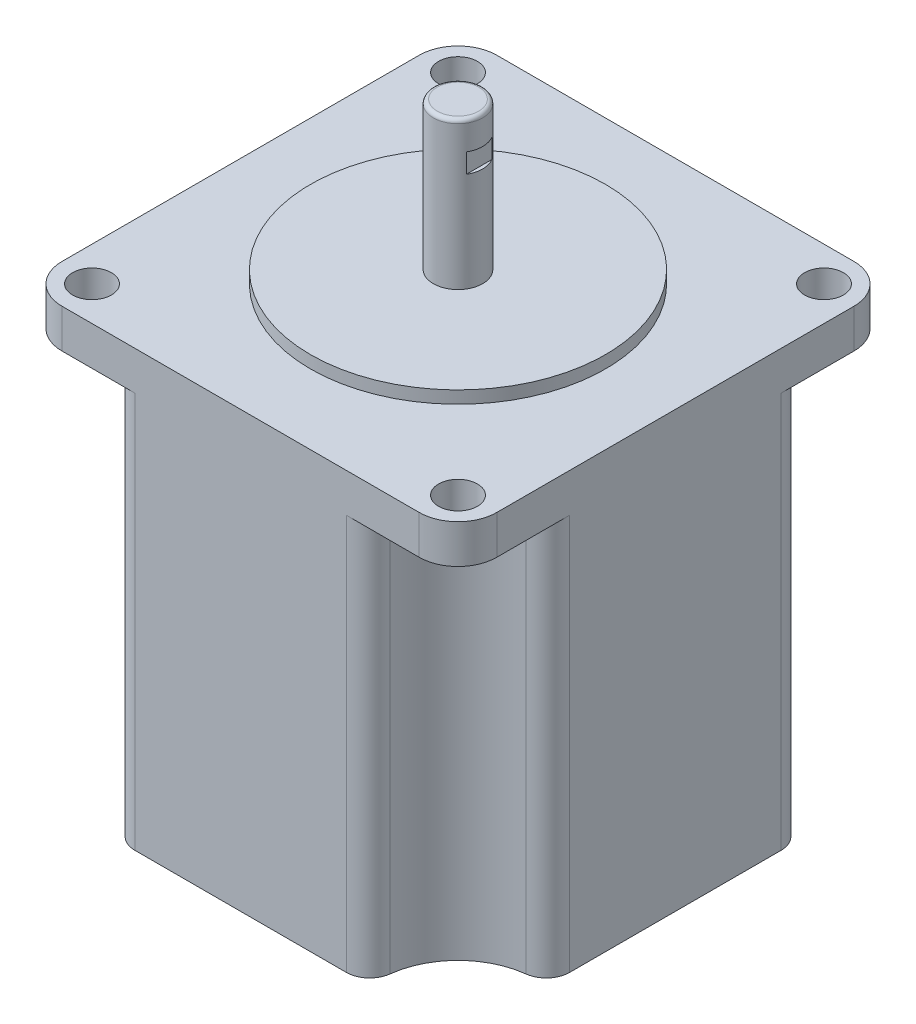
SolidWorks part; units mm, degrees
ref_plane "Front Plane" through (0, 0, 0) normal (0, 0, 1) x (1, 0, 0)
ref_plane "Top Plane" through (0, 0, 0) normal (0, 1, 0) x (1, 0, 0)
ref_plane "Right Plane" through (0, 0, 0) normal (1, 0, 0) x (0, 0, -1)
sketch "Sketch1" plane through (0, 0, 0) normal (0, 1, 0) x (1, 0, 0)
  line L1 (-23, 28) -> (23, 28)
  line L2 (-28, 23) -> (-28, -23)
  line L3 (-23, -28) -> (23, -28)
  line L4 (28, 23) -> (28, -23)
  line L5 (-28, 28) -> (28, -28) construction
  line L6 (-28, -28) -> (28, 28) construction
  arc A0 (-28, 23) -> (-23, 28) centre (-23, 23) cw
  arc A1 (28, 23) -> (23, 28) centre (23, 23) ccw
  arc A2 (23, -28) -> (28, -23) centre (23, -23) ccw
  arc A3 (-28, -23) -> (-23, -28) centre (-23, -23) ccw
  point P0 (0, 0)
  dimension "D1" = 5
extrude "Extrude1" add sketch "Sketch1" along normal blind 56
sketch "Sketch2" plane through (0, 0, 0) normal (0, -1, 0) x (1, 0, 0)
  line L0 (-28, 0) -> (-48.8834, 0) construction
  line L2 (0, 28) -> (0, 39.893) construction
  circle A0 centre (23.57, 23.57) radius 2.5
  circle A1 centre (23.57, -23.57) radius 2.5
  circle A2 centre (-23.57, -23.57) radius 2.5
  circle A4 centre (-23.57, 23.57) radius 2.5
  dimension "D1" = 23.57
  dimension "D2" = 23.57
extrude "Extrude2" cut sketch "Sketch2" against normal through all
sketch "Sketch4" plane through (0, 0, 0) normal (0, -1, 0) x (1, 0, 0)
  line L0 (0, 28) -> (0, 30.6048) construction
  line L2 (-28, 0) -> (-33.0561, 0) construction
  circle A0 centre (-26.5355, 26.5355) radius 10
  arc A1 (-23, 28) -> (-28, 23) centre (-23, 23) ccw construction
  circle A2 centre (26.5355, 26.5355) radius 10
  circle A3 centre (26.5355, -26.5355) radius 10
  circle A4 centre (-26.5355, -26.5355) radius 10
extrude "Extrude3" cut sketch "Sketch4" against normal blind 51
fillet "Fillet1" radius 3 8 edges at (-16.6433, 25.5, -28) (-28, 25.5, -16.6433) (16.6433, 25.5, -28) (28, 25.5, -16.6433) (28, 25.5, 16.6433) (16.6433, 25.5, 28) (-16.6433, 25.5, 28) (-28, 25.5, 16.6433)
sketch "Sketch5" plane through (0, 56, 0) normal (0, 1, 0) x (1, 0, 0)
  circle A0 centre (0, 0) radius 19
extrude "Extrude4" add sketch "Sketch5" along normal blind 1.6
sketch "Sketch6" plane through (0, 56, 0) normal (0, 1, 0) x (1, 0, 0)
  circle A0 centre (0, 0) radius 3.175
extrude "Extrude5" add sketch "Sketch6" along normal blind 20.6
fillet "Fillet2" radius 0.5 1 edges at (0, 76.6, 3.175)
ref_plane "Плоскость1" through (0, 70.4, 0) normal (0, 1, 0) x (-1, 0, 0)
sketch "Эскиз1" plane through (0, 70.4, 0) normal (0, 1, 0) x (-1, 0, 0)
  line L0 (0, 0) -> (0, -5.6994) construction
  line L1 (3.4735, -1.6391) -> (3.4735, 1.7925)
  line L2 (-2.7192, -1.6391) -> (-3.4735, -1.6391)
  line L3 (-2.7192, -1.6391) -> (-2.7192, 1.7925)
  line L4 (-2.7192, 1.7925) -> (-3.4735, 1.7925)
  line L5 (-3.4735, -1.6391) -> (-3.4735, 1.7925)
  line L6 (2.7192, 1.7925) -> (3.4735, 1.7925)
  line L7 (2.7192, -1.6391) -> (2.7192, 1.7925)
  line L8 (2.7192, -1.6391) -> (3.4735, -1.6391)
  circle A0 centre (0, 0) radius 3.175 construction
extrude "Вытянуть1" cut sketch "Эскиз1" along normal blind 2.5
